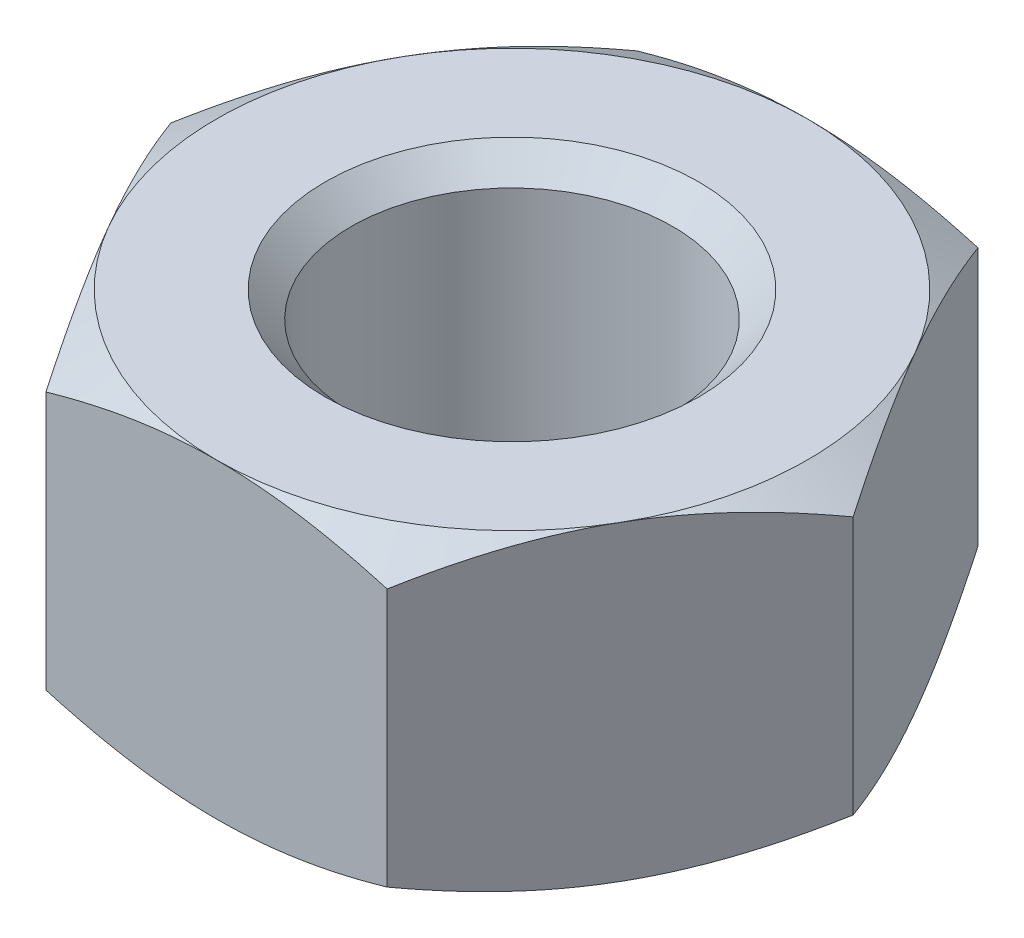
SolidWorks part; units mm, degrees
material "1.0050 (E295)"
ref_plane "Спереди" through (0, 0, 0) normal (0, 0, 1) x (1, 0, 0)
ref_plane "Сверху" through (0, 0, 0) normal (0, 1, 0) x (1, 0, 0)
ref_plane "Справа" through (0, 0, 0) normal (1, 0, 0) x (0, 0, -1)
sketch "Эскиз1" plane through (0, 0, 0) normal (0, 1, 0) x (1, 0, 0)
  line L1 (-5.4848, 9.5) -> (-10.9697, 0)
  line L2 (-10.9697, 0) -> (-5.4848, -9.5)
  line L3 (-5.4848, -9.5) -> (5.4848, -9.5)
  line L4 (5.4848, -9.5) -> (10.9697, 0)
  line L5 (10.9697, 0) -> (5.4848, 9.5)
  line L6 (5.4848, 9.5) -> (-5.4848, 9.5)
  circle A0 centre (0, 0) radius 9.5 construction
  dimension "D1" = 19
extrude "Бобышка-Вытянуть1" add sketch "Эскиз1" along normal blind 10
sketch "Эскиз2" plane through (0, 0, 0) normal (1, 0, 0) x (0, 0, -1)
  line L0 (-9.5, 10) -> (-10.97, 10)
  line L1 (-10.97, 10) -> (-10.97, 9.1513)
  line L2 (-10.97, 9.1513) -> (-9.5, 10)
  line L3 (0, -1000) -> (0, 49000) construction
  line L4 (-9.5, 0) -> (-10.97, 0)
  line L5 (-10.97, 0) -> (-10.97, 0.8487)
  line L6 (-10.97, 0.8487) -> (-9.5, 0)
  dimension "D1" = 30
  dimension "D2" = 1.47
  dimension "D3" = 30
revolve "Вырез-Повернуть1" cut sketch "Эскиз2" angle 360 about L3
sketch "Эскиз4" plane through (0, 0, 0) normal (0, -1, 0) x (1, 0, 0)
  circle A0 centre (0, 0) radius 5.17
  dimension "D1" = 10.34
extrude "Вырез-Вытянуть1" cut sketch "Эскиз4" against normal blind 10
cosmetic thread "Условное изображение резьбы1" parameters "D2"=12
chamfer "Фаска1" distance 0.83 angle 45 2 edges at (0, 10, -5.17) (0, 0, -5.17)
